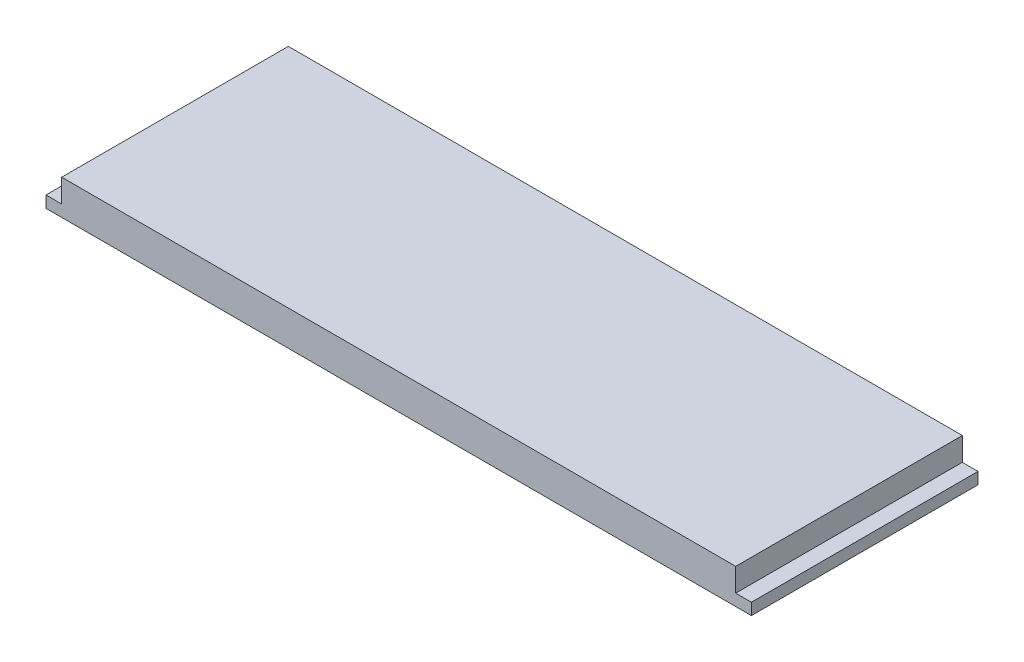
SolidWorks part; units mm, degrees
ref_plane "Front Plane" through (0, 0, 0) normal (0, 0, 1) x (1, 0, 0)
ref_plane "Top Plane" through (0, 0, 0) normal (0, 1, 0) x (1, 0, 0)
ref_plane "Right Plane" through (0, 0, 0) normal (1, 0, 0) x (0, 0, -1)
sketch "Sketch1" plane through (0, 0, 0) normal (0, 1, 0) x (1, 0, 0)
  line L1 (0, 0) -> (60.7, 0)
  line L2 (0, 0) -> (0, -19.5)
  line L3 (0, -19.5) -> (60.7, -19.5)
  line L4 (60.7, 0) -> (60.7, -19.5)
  dimension "D1" = 19.5
  dimension "D2" = 60.7
extrude "Boss-Extrude1" add sketch "Sketch1" along normal blind 1
sketch "Sketch2" plane through (0, 1, 0) normal (0, 1, 0) x (1, 0, 0)
  line L1 (1.35, 0) -> (59.35, 0)
  line L2 (1.35, 0) -> (1.35, -19.5)
  line L3 (1.35, -19.5) -> (59.35, -19.5)
  line L4 (59.35, 0) -> (59.35, -19.5)
  line L6 (60.7, 0) -> (0, 0) construction
  line L7 (0, -19.5) -> (60.7, -19.5) construction
  point P8 (30.35, 0)
  dimension "D1" = 19.5
  dimension "D2" = 58
extrude "Boss-Extrude2" add sketch "Sketch2" along normal blind 2
